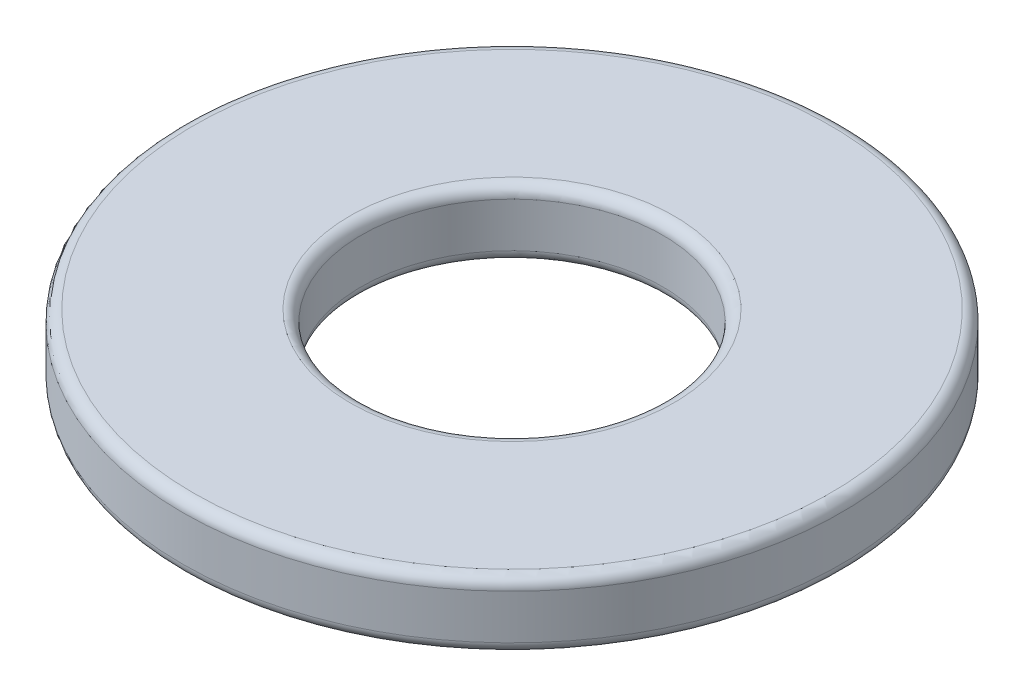
SolidWorks part; units mm, degrees
ref_plane "Front Plane" through (0, 0, 0) normal (0, 0, 1) x (1, 0, 0)
ref_plane "Top Plane" through (0, 0, 0) normal (0, 1, 0) x (1, 0, 0)
ref_plane "Right Plane" through (0, 0, 0) normal (1, 0, 0) x (0, 0, -1)
sketch "Main Sketch" plane through (0, 0, 0) normal (0, 1, 0) x (1, 0, 0)
  circle A0 centre (0, 0) radius 2.7
  circle A1 centre (0, 0) radius 5.9
  dimension "D1" = 5.4
  dimension "D2" = 11.8
extrude "Washer Main" add sketch "Main Sketch" along normal blind 1.2
fillet "Edge Fillets" radius 0.2 4 edges at (0, 0, 5.9) (0, 1.2, 5.9) (0, 0, 2.7) (0, 1.2, 2.7)
